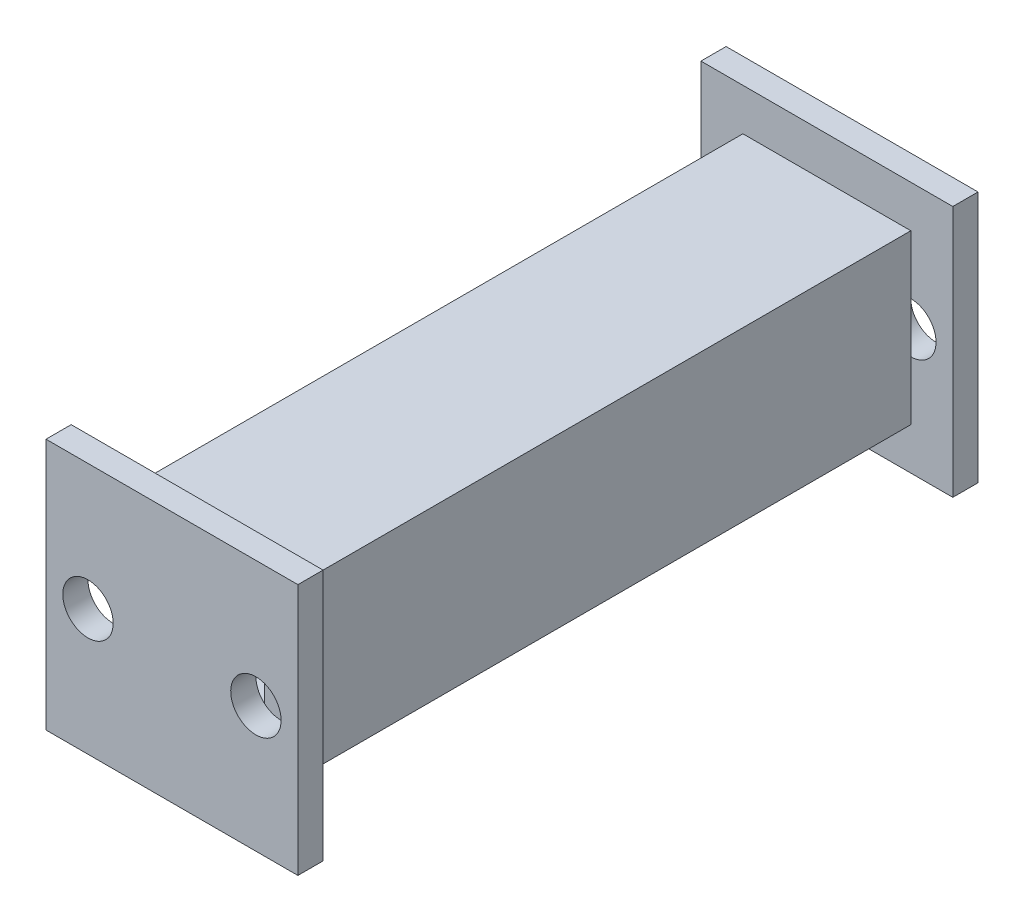
SolidWorks part; units mm, degrees
ref_plane "前视基准面" through (0, 0, 0) normal (0, 0, 1) x (1, 0, 0)
ref_plane "上视基准面" through (0, 0, 0) normal (0, 1, 0) x (1, 0, 0)
ref_plane "右视基准面" through (0, 0, 0) normal (1, 0, 0) x (0, 0, -1)
other "Configuration Table"
sketch "草图8" plane through (0, 0, 0) normal (0, 0, 1) x (1, 0, 0)
  line L1 (-40, 40) -> (40, 40)
  line L2 (-40, 40) -> (-40, -40)
  line L3 (-40, -40) -> (40, -40)
  line L4 (40, 40) -> (40, -40)
  line L5 (-32, 32) -> (32, 32)
  line L6 (-32, 32) -> (-32, -32)
  line L7 (-32, -32) -> (32, -32)
  line L8 (32, 32) -> (32, -32)
extrude "凸台-拉伸1" add sketch "草图8" along normal mid plane 300
sketch "草图9" plane through (0, 0, 150) normal (0, 0, 1) x (1, 0, 0)
  line L1 (-60, 60) -> (60, 60)
  line L2 (-60, 60) -> (-60, -60)
  line L3 (-60, -60) -> (60, -60)
  line L4 (60, 60) -> (60, -60)
  circle A0 centre (40, 0) radius 12
  circle A1 centre (-40, 0) radius 12
extrude "凸台-拉伸2" add sketch "草图9" along normal blind 12
sketch "草图10" plane through (0, 0, -150) normal (0, 0, -1) x (-1, 0, 0)
  line L1 (-60, 60) -> (60, 60)
  line L2 (-60, 60) -> (-60, -60)
  line L3 (-60, -60) -> (60, -60)
  line L4 (60, 60) -> (60, -60)
  circle A0 centre (40, 0) radius 12
  circle A1 centre (-40, 0) radius 12
extrude "凸台-拉伸3" add sketch "草图10" along normal blind 12
